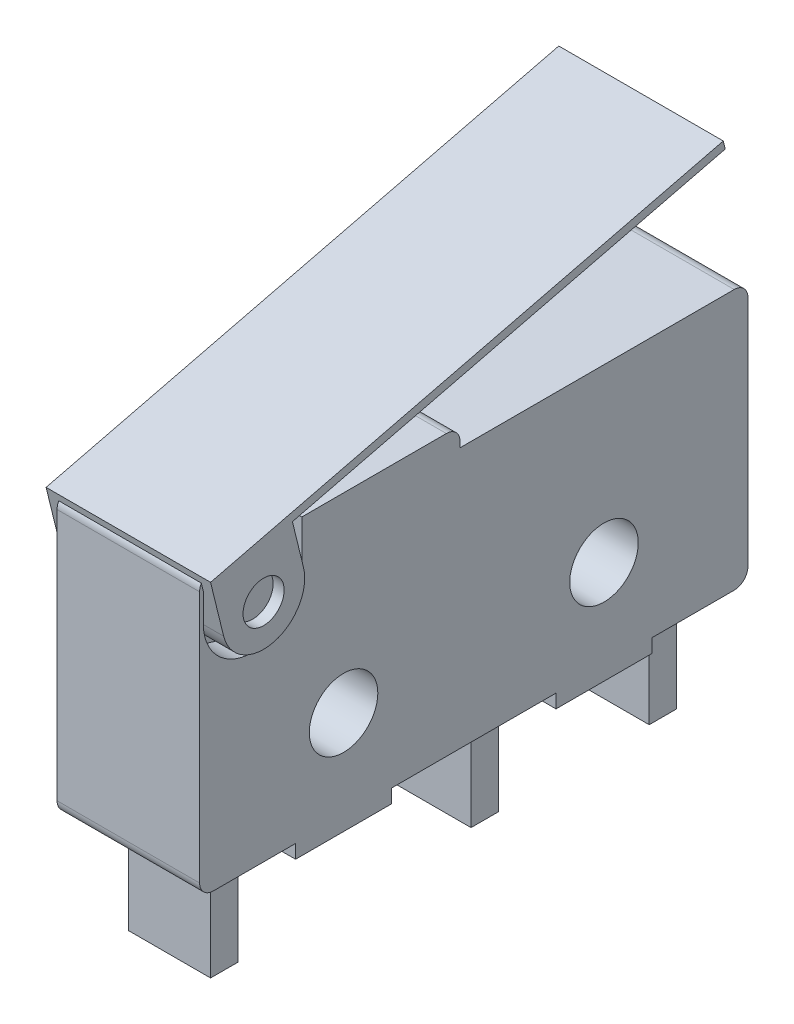
SolidWorks part; units mm, degrees
ref_plane "Front Plane" through (0, 0, 0) normal (0, 0, 1) x (1, 0, 0)
ref_plane "Top Plane" through (0, 0, 0) normal (0, 1, 0) x (1, 0, 0)
ref_plane "Right Plane" through (0, 0, 0) normal (1, 0, 0) x (0, 0, -1)
sketch "Sketch1" plane through (0, 0, 0) normal (1, 0, 0) x (0, 0, -1)
  line L0 (9.5, 10.2) -> (9.5, 9.5)
  line L1 (0, 0) -> (3.5, 0)
  line L2 (0, 0) -> (0, 10.2)
  line L3 (0, 10.2) -> (9.5, 10.2)
  line L4 (20, 0) -> (20, 9.5)
  line L5 (9.5, 9.5) -> (20, 9.5)
  line L6 (3.5, 0) -> (3.5, -0.5)
  line L7 (3.5, -0.5) -> (7, -0.5)
  line L8 (7, -0.5) -> (7, 0)
  line L9 (13, 0) -> (13, -0.5)
  line L10 (13, -0.5) -> (16.5, -0.5)
  line L11 (16.5, -0.5) -> (16.5, 0)
  line L12 (7, 0) -> (13, 0)
  line L13 (16.5, 0) -> (20, 0)
  line L14 (0, 3.25) -> (20, 3.25) construction
  circle A0 centre (5.25, 3.25) radius 1.25
  circle A1 centre (14.75, 3.25) radius 1.25
  point P21 (4, 3.25)
  point P22 (16, 3.25)
  point P23 (14.75, 4.5)
  dimension "D9" = 2.5
  dimension "D1" = 20
  dimension "D2" = 10.2
  dimension "D3" = 9.5
  dimension "D4" = 9.5
  dimension "D5" = 3.5
  dimension "D6" = 3.5
  dimension "D7" = 3.5
  dimension "D8" = 0.5
  dimension "D10" = 4
  dimension "D11" = 4
  dimension "D12" = 5
extrude "Boss-Extrude1" add sketch "Sketch1" along normal mid plane 5.2
sketch "Sketch2" plane through (0, 0, 0) normal (1, 0, 0) x (0, 0, -1)
  line L0 (0, 0) -> (3.5, 0) construction
  line L1 (1.5, 0) -> (2.5, 0)
  line L2 (1.5, 0) -> (1.5, -3.8)
  line L3 (1.5, -3.8) -> (2.5, -3.8)
  line L4 (2.5, 0) -> (2.5, -3.8)
  line L5 (11, 0) -> (12, 0)
  line L6 (11, 0) -> (11, -3.8)
  line L7 (11, -3.8) -> (12, -3.8)
  line L8 (12, 0) -> (12, -3.8)
  line L9 (17.5, 0) -> (18.5, 0)
  line L10 (17.5, 0) -> (17.5, -3.8)
  line L11 (17.5, -3.8) -> (18.5, -3.8)
  line L12 (18.5, 0) -> (18.5, -3.8)
  line L13 (0, 10.2) -> (0, 0) construction
  line L14 (20, 0) -> (20, 9.5) construction
  line L15 (16.5, 0) -> (20, 0) construction
  dimension "D1" = 3.8
  dimension "D2" = 1.5
  dimension "D3" = 1
  dimension "D4" = 1.5
  dimension "D5" = 6.5
extrude "Boss-Extrude2" add sketch "Sketch2" along normal mid plane 3 separate body
sketch "Sketch3" plane through (0, 0, 0) normal (1, 0, 0) x (0, 0, -1)
  line L0 (0.4769, 8.2577) -> (0, 10.2)
  line L1 (0, 10.2) -> (18.7009, 14.7913)
  line L2 (18.7009, 14.7913) -> (18.7724, 14.5)
  line L3 (18.7724, 14.5) -> (2.985, 10.624)
  line L4 (2.985, 10.624) -> (3.3903, 8.973)
  line L5 (20, 9.5) -> (9.5, 9.5) construction
  line L6 (2.2913, 7.1586) -> (1.9336, 8.6153) construction
  arc A0 (0.4769, 8.2577) -> (3.3903, 8.973) centre (1.9336, 8.6153) ccw
  circle A1 centre (1.9336, 8.6153) radius 0.75
  circle A2 centre (1.9336, 8.6153) radius 17.5 construction
  point P12 (2.2913, 7.1586)
  dimension "D2" = 1.5
  dimension "D7" = 35
  dimension "D1" = 3
  dimension "D3" = 0.3
  dimension "D4" = 5
  dimension "D5" = 3.5
  dimension "D6" = 2
fillet "Fillet1" radius 0.5 5 edges at (0, 10.2, -9.5) (0, 0, -20) (0, 9.5, -20) (0, 0, 0) (0, 10.2, 0)
extrude "Boss-Extrude3" add sketch "Sketch3" along normal mid plane 6 separate body
sketch "Sketch4" plane through (2.6, 0, 0) normal (1, 0, 0) x (0, 0, -1)
  line L0 (1.9336, 8.6153) -> (1.9336, 12.6213) construction
  line L1 (0.136, 8.6153) -> (0.136, 12.6213)
  line L2 (3.7312, 8.6153) -> (3.7312, 12.6213)
  arc A0 (0.136, 8.6153) -> (3.7312, 8.6153) centre (1.9336, 8.6153) ccw
  circle A1 centre (1.9336, 8.6153) radius 0.75
  circle A2 centre (1.9336, 8.6153) radius 0.75
  arc A5 (3.7312, 12.6213) -> (0.136, 12.6213) centre (1.9336, 12.6213) ccw
  point P0 (1.9336, 10.6183)
  dimension "D2" = 1.7976
  dimension "D1" = 0
extrude "Cut-Extrude1" cut sketch "Sketch4" against normal blind 1
mirror "Mirror2" about plane through (0, 0, 0) normal (1, 0, 0) of "Cut-Extrude1"
